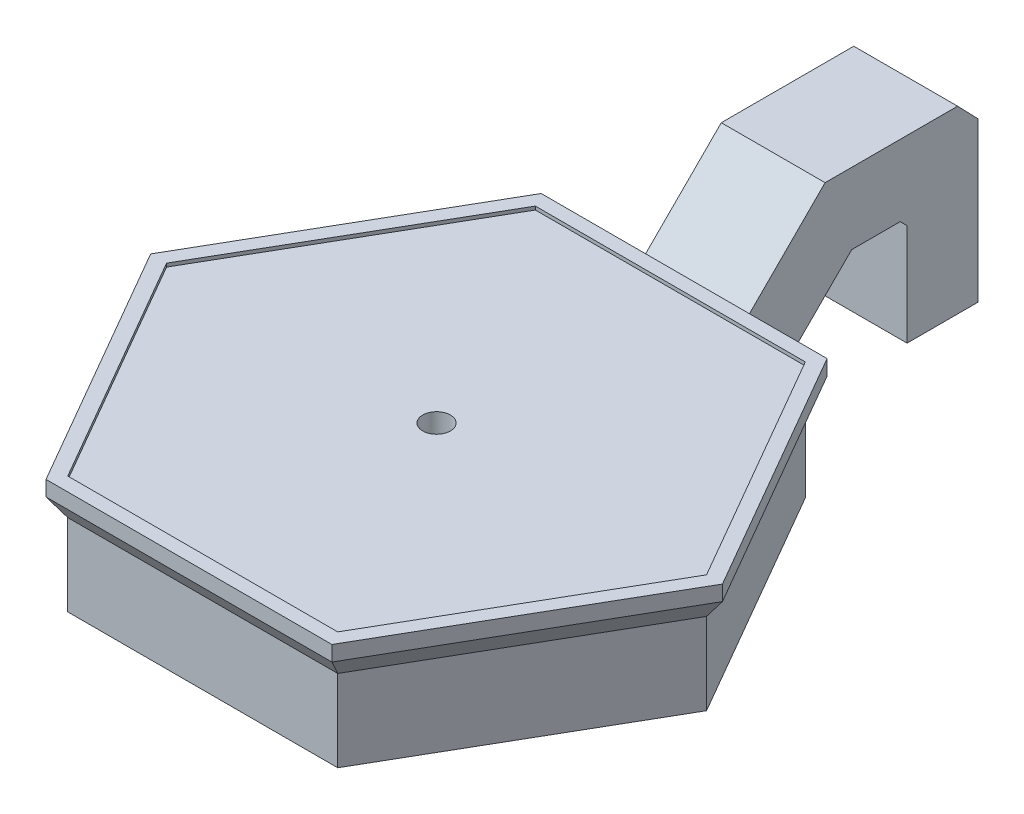
SolidWorks part; units mm, degrees
ref_plane "Alzado" through (0, 0, 0) normal (0, 0, 1) x (1, 0, 0)
ref_plane "Planta" through (0, 0, 0) normal (0, 1, 0) x (1, 0, 0)
ref_plane "Vista lateral" through (0, 0, 0) normal (1, 0, 0) x (0, 0, -1)
sketch "Croquis1" plane through (0, 0, 0) normal (0, 1, 0) x (1, 0, 0)
  line L0 (-55, 0) -> (55, 0) construction
  line L1 (19.5, -33.775) -> (39, 0)
  line L2 (39, 0) -> (19.5, 33.775)
  line L3 (19.5, 33.775) -> (-19.5, 33.775)
  line L4 (-19.5, 33.775) -> (-39, 0)
  line L5 (-39, 0) -> (-19.5, -33.775)
  line L6 (-19.5, -33.775) -> (19.5, -33.775)
  circle A0 centre (0, 0) radius 33.775 construction
  dimension "D1" = 39
extrude "Saliente-Extruir1" add sketch "Croquis1" along normal blind 11.8
ref_plane "Plano1" through (0, 14.8, 0) normal (0, 1, 0) x (1, 0, 0)
sketch "Croquis4" plane through (0, 14.8, 0) normal (0, 1, 0) x (1, 0, 0)
  line L0 (-8.1401, 0) -> (8.1401, 0) construction
  line L1 (20.65, -35.7668) -> (41.3, 0)
  line L2 (41.3, 0) -> (20.65, 35.7668)
  line L3 (20.65, 35.7668) -> (-20.65, 35.7668)
  line L4 (-20.65, 35.7668) -> (-41.3, 0)
  line L5 (-41.3, 0) -> (-20.65, -35.7668)
  line L6 (-20.65, -35.7668) -> (20.65, -35.7668)
  circle A0 centre (0, 0) radius 35.7668 construction
  dimension "D1" = 41.3
loft "Recubrir2" add profiles "Croquis4" section face at (0, 11.8, 0) section "Croquis4"
sketch "Croquis5" plane through (0, 14.8, 0) normal (0, 1, 0) x (1, 0, 0)
  line L1 (20.65, -35.7668) -> (41.3, 0)
  line L2 (41.3, 0) -> (20.65, 35.7668)
  line L3 (20.65, 35.7668) -> (-20.65, 35.7668)
  line L4 (-20.65, 35.7668) -> (-41.3, 0)
  line L5 (-41.3, 0) -> (-20.65, -35.7668)
  line L6 (-20.65, -35.7668) -> (20.65, -35.7668)
  circle A0 centre (0, 0) radius 35.7668 construction
extrude "Saliente-Extruir2" add sketch "Croquis5" along normal blind 2.2 contours L1 L2 L3 L4 L5 L6
sketch "Croquis6" plane through (0, 17, 0) normal (0, 1, 0) x (1, 0, 0)
  line L0 (-9.35, 0) -> (9.35, 0) construction
  line L1 (19.5, -33.775) -> (39, 0)
  line L2 (39, 0) -> (19.5, 33.775)
  line L3 (19.5, 33.775) -> (-19.5, 33.775)
  line L4 (-19.5, 33.775) -> (-39, 0)
  line L5 (-39, 0) -> (-19.5, -33.775)
  line L6 (-19.5, -33.775) -> (19.5, -33.775)
  circle A0 centre (0, 0) radius 33.775 construction
  dimension "D1" = 39
extrude "Cortar-Extruir1" cut sketch "Croquis6" against normal blind 0.5
sketch "Croquis7" plane through (0, 16.5, 0) normal (0, 1, 0) x (1, 0, 0)
  circle A0 centre (0, 0) radius 2
  dimension "D1" = 4
extrude "Cortar-Extruir2" cut sketch "Croquis7" against normal through all
sketch "Croquis8" plane through (0, 0, 0) normal (1, 0, 0) x (0, 0, -1)
  line L0 (36.775, 0) -> (52.4728, 15.6978)
  line L1 (33.775, 11.8) -> (34.4329, 11.8)
  line L2 (33.775, 11.8) -> (33.775, 0)
  line L3 (33.775, 0) -> (36.775, 0)
  line L5 (34.4329, 11.8) -> (48.6316, 25.9987)
  line L6 (48.6316, 25.9987) -> (67.7716, 25.9987)
  line L7 (52.4728, 15.6978) -> (59.4728, 15.6978)
  line L8 (67.7716, 25.9987) -> (70.7169, 22.9487)
  line L9 (59.4728, 15.6978) -> (60.4698, 14.7007)
  line L10 (70.7169, 22.9487) -> (70.7169, 0)
  line L11 (70.7169, 0) -> (60.4698, 0)
  line L12 (60.4698, 0) -> (60.4698, 14.7007)
  dimension "D1" = 3
  dimension "D2" = 135
  dimension "D3" = 22.2
  dimension "D4" = 0.6579
  dimension "D5" = 20.08
  dimension "D6" = 19.14
  dimension "D7" = 7
  dimension "D8" = 134
  dimension "D9" = 4.24
  dimension "D10" = 1.41
extrude "Saliente-Extruir3" add sketch "Croquis8" along normal mid plane 15 contours L12 L9 L7 L0 L3 L2 L1 L5 L6 L8 L10 L11
